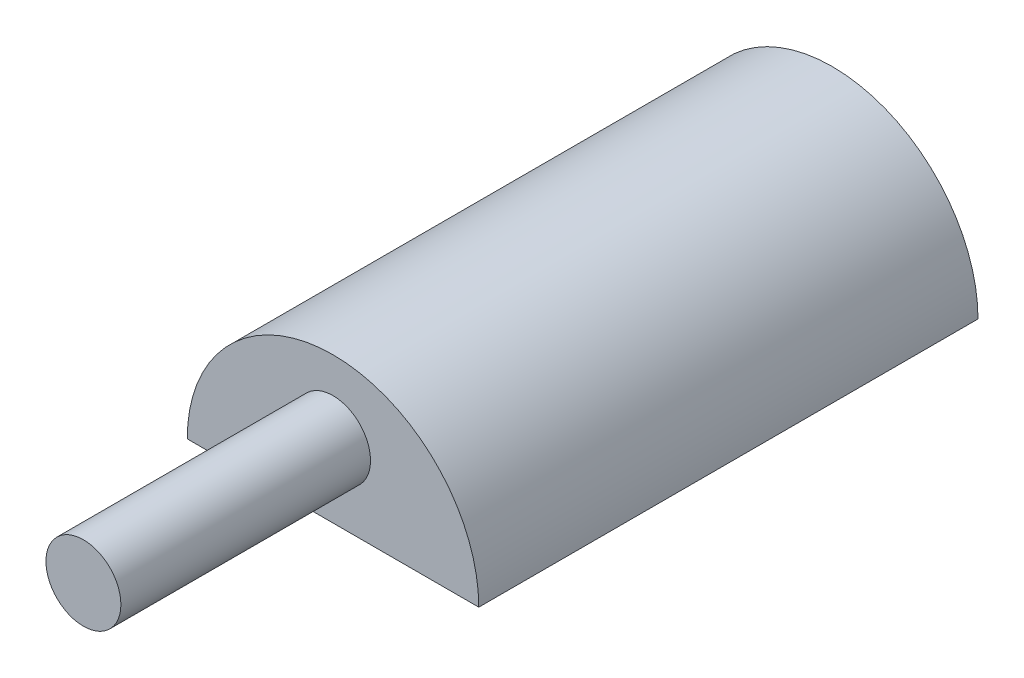
SolidWorks part; units mm, degrees
ref_plane "Alzado" through (0, 0, 0) normal (0, 0, 1) x (1, 0, 0)
ref_plane "Planta" through (0, 0, 0) normal (0, 1, 0) x (1, 0, 0)
ref_plane "Vista lateral" through (0, 0, 0) normal (1, 0, 0) x (0, 0, -1)
sketch "Croquis1" plane through (0, 0, 0) normal (0, 0, 1) x (1, 0, 0)
  line L0 (0, 0) -> (-74.168, 0)
  line L1 (0, 0) -> (74.168, 0)
  arc A0 (74.168, 0) -> (-74.168, 0) centre (0, 0) ccw
extrude "Saliente-Extruir1" add sketch "Croquis1" along normal blind 254
sketch "Croquis2" plane through (0, 0, 254) normal (0, 0, 1) x (1, 0, 0)
  line L0 (0, 0) -> (0, 74.168)
  arc A0 (74.168, 0) -> (-74.168, 0) centre (0, 0) ccw construction
  circle A1 centre (0, 37.084) radius 19.0697
extrude "Saliente-Extruir2" add sketch "Croquis2" along normal blind 127 contours A1
